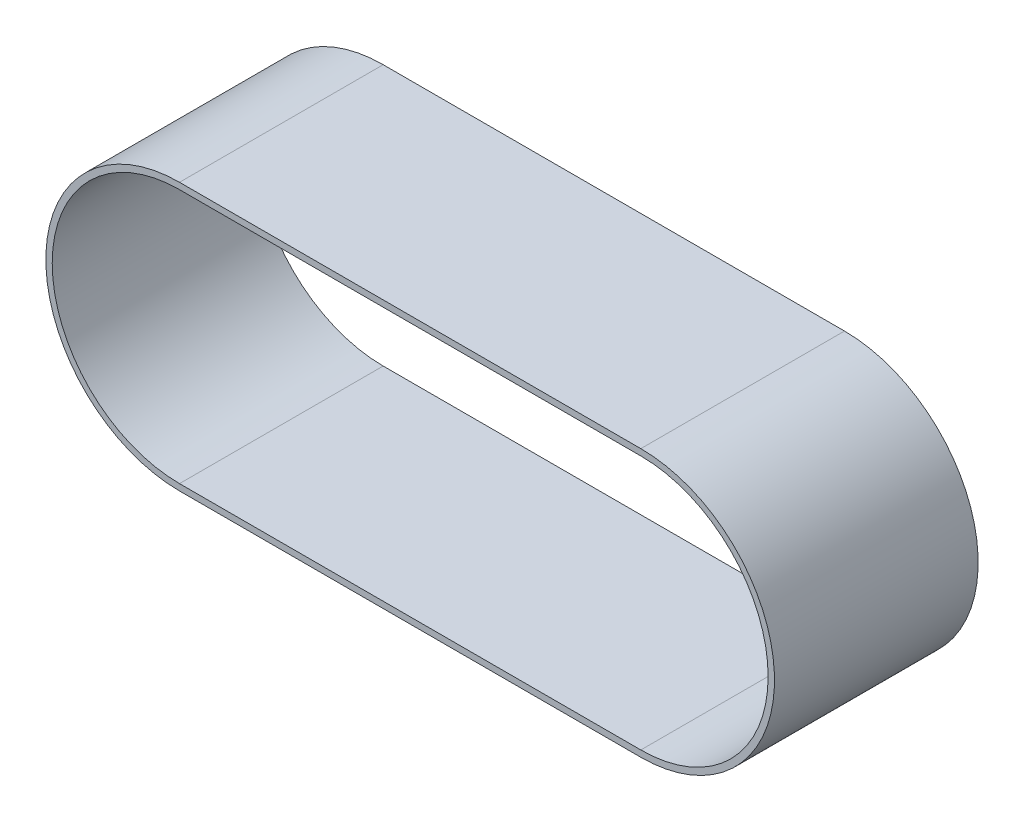
SolidWorks part; units mm, degrees
material "POLYURETHANE (11671)"
ref_plane "Front Plane" through (0, 0, 0) normal (0, 0, 1) x (1, 0, 0)
ref_plane "Top Plane" through (0, 0, 0) normal (0, 1, 0) x (1, 0, 0)
ref_plane "Right Plane" through (0, 0, 0) normal (1, 0, 0) x (0, 0, -1)
sketch "Sketch1" plane through (0, 0, 0) normal (0, 0, 1) x (1, 0, 0)
  line L0 (0, 0) -> (115.062, 0) construction
  line L1 (0, 31.75) -> (115.062, 31.75)
  line L2 (0, -31.75) -> (115.062, -31.75)
  line L3 (0, 0) -> (115.062, 0) construction
  line L4 (0, 33.3375) -> (115.062, 33.3375)
  line L5 (0, -33.3375) -> (115.062, -33.3375)
  arc A0 (0, 31.75) -> (0, -31.75) centre (0, 0) ccw
  arc A1 (115.062, -31.75) -> (115.062, 31.75) centre (115.062, 0) ccw
  arc A2 (0, 33.3375) -> (0, -33.3375) centre (0, 0) ccw
  arc A3 (115.062, -33.3375) -> (115.062, 33.3375) centre (115.062, 0) ccw
  point P3 (57.531, 0)
  point P10 (57.531, 0)
  dimension "D2" = 63.5
  dimension "D3" = 66.675
  dimension "D1" = 115.062
extrude "Boss-Extrude1" add sketch "Sketch1" along normal blind 50.8
